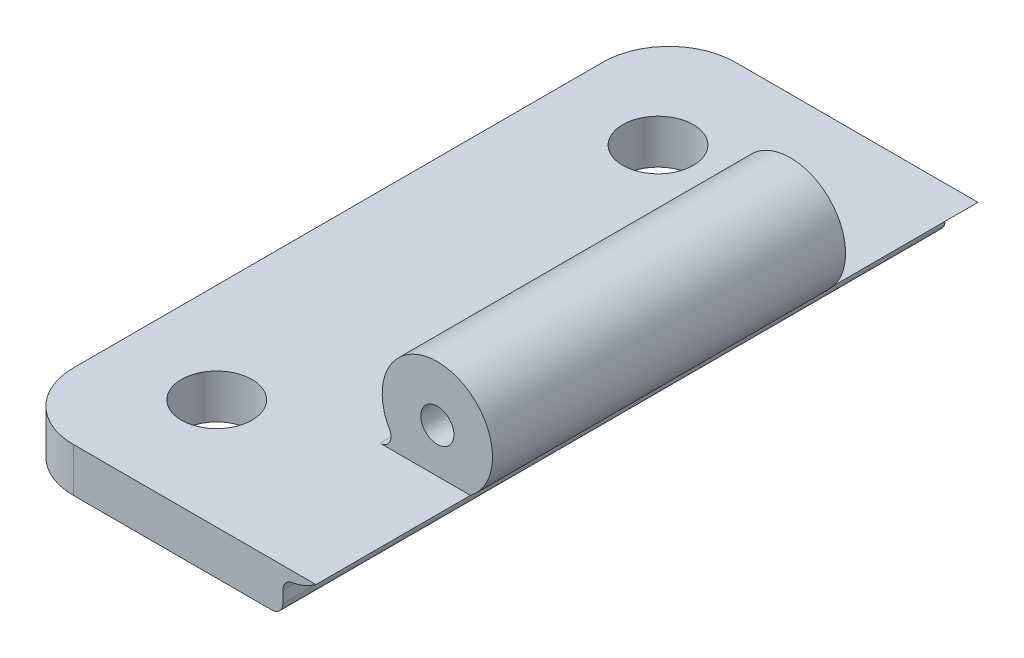
SolidWorks part; units mm, degrees
ref_plane "前视基准面" through (0, 0, 0) normal (0, 0, 1) x (1, 0, 0)
ref_plane "上视基准面" through (0, 0, 0) normal (0, 1, 0) x (1, 0, 0)
ref_plane "右视基准面" through (0, 0, 0) normal (1, 0, 0) x (0, 0, -1)
other "Configuration Table"
sketch "草图1" plane through (0, 0, 0) normal (0, 1, 0) x (1, 0, 0)
  line L1 (3, 0) -> (12.5, 0)
  line L2 (0, -3) -> (0, -27)
  line L3 (3, -30) -> (12.5, -30)
  line L4 (12.5, 0) -> (12.5, -30)
  circle A0 centre (4.5, -5) radius 1.6
  circle A1 centre (4.5, -25) radius 1.6
  arc A2 (0, -27) -> (3, -30) centre (3, -27) ccw
  arc A3 (3, 0) -> (0, -3) centre (3, -3) ccw
  point P9 (12.5, -15)
  point P12 (0, -30)
  point P15 (0, 0)
  dimension "D3" = 3.2
  dimension "D4" = 3.2
  dimension "D9" = 3
  dimension "D1" = 12.5
  dimension "D2" = 30
  dimension "D5" = 8
  dimension "D6" = 8
  dimension "D7" = 10
  dimension "D8" = 10
extrude "凸台-拉伸1" add sketch "草图1" along normal blind 2
sketch "草图2" plane through (0, 0, 30) normal (0, 0, 1) x (1, 0, 0)
  line L0 (12.5, 2) -> (12.5, 0) construction
  line L1 (3, 0) -> (12.5, 0) construction
  circle A0 centre (12.5, 4) radius 2.5
  dimension "D1" = 5
  dimension "D2" = 4
extrude "凸台-拉伸2" add sketch "草图2" against normal up to surface (30 mm away) contours A0 up to face at (7.75, 1, 0)
fillet "圆角1" radius 0.5 3 edges at (11, 2, 15) (12.5, 0, 15) (12.5, 1.5, 15)
sketch "草图3" plane through (0, 0, 30) normal (0, 0, 1) x (1, 0, 0)
  circle A0 centre (12.5, 4) radius 0.75
  dimension "D1" = 1.5
extrude "切除-拉伸1" cut sketch "草图3" against normal through all
sketch "草图4" plane through (0, 2, 0) normal (0, 1, 0) x (1, 0, 0)
  line L0 (15, -30) -> (15, 0) construction
  line L5 (9.9019, 0) -> (15, 0)
  line L6 (9.9019, 0) -> (9.9019, -7)
  line L7 (9.9019, -7) -> (15, -7)
  line L16 (15, 0) -> (15, -7)
  line L17 (9.9019, -30) -> (9.9019, 0) construction
  line L18 (9.9019, -23) -> (15, -23)
  line L19 (9.9019, -23) -> (9.9019, -30)
  line L20 (9.9019, -30) -> (15, -30)
  line L21 (15, -23) -> (15, -30)
  dimension "D1" = 7
  dimension "D2" = 7
extrude "切除-拉伸2" cut sketch "草图4" along normal through all
